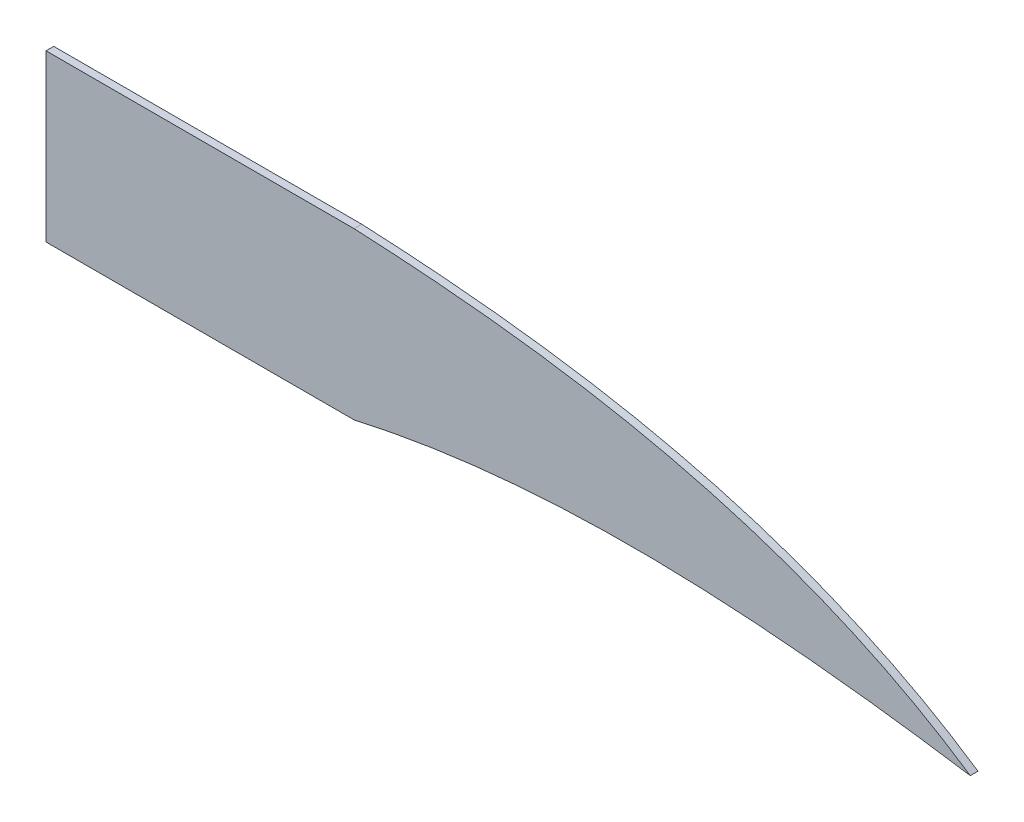
SolidWorks part; units mm, degrees
ref_plane "Front Plane" through (0, 0, 0) normal (0, 0, 1) x (1, 0, 0)
ref_plane "Top Plane" through (0, 0, 0) normal (0, 1, 0) x (1, 0, 0)
ref_plane "Right Plane" through (0, 0, 0) normal (1, 0, 0) x (0, 0, -1)
sketch "Sketch1" plane through (0, 0, 0) normal (0, 0, 1) x (1, 0, 0)
  line L0 (-120, 21.5) -> (-40, 21.5)
  line L1 (120, -21.5) -> (-120, -21.5) construction
  line L2 (120, -21.5) -> (120, 21.5) construction
  line L3 (120, 21.5) -> (-120, 21.5) construction
  line L4 (-120, -21.5) -> (-120, 21.5) construction
  line L5 (120, -21.5) -> (-120, 21.5) construction
  line L6 (120, 21.5) -> (-120, -21.5) construction
  line L7 (-120, -21.5) -> (-40, -21.5)
  line L8 (-120, 21.5) -> (-120, -21.5)
  spline S0 degree 3 poles (-40, 21.5) (15.0755, 18.9258) (73.2532, 10.0303) (120, -21.5) knots 0 0 0 0 1 1 1 1
  spline S1 degree 3 poles (-40, -21.5) (12.7785, -9.523) (67.1413, -13.4062) (120, -21.5) knots 0 0 0 0 1 1 1 1
  point P1 (0, 0)
  dimension "D1" = 240
  dimension "D2" = 43
  dimension "D3" = 80
extrude "Boss-Extrude1" add sketch "Sketch1" along normal blind 2
